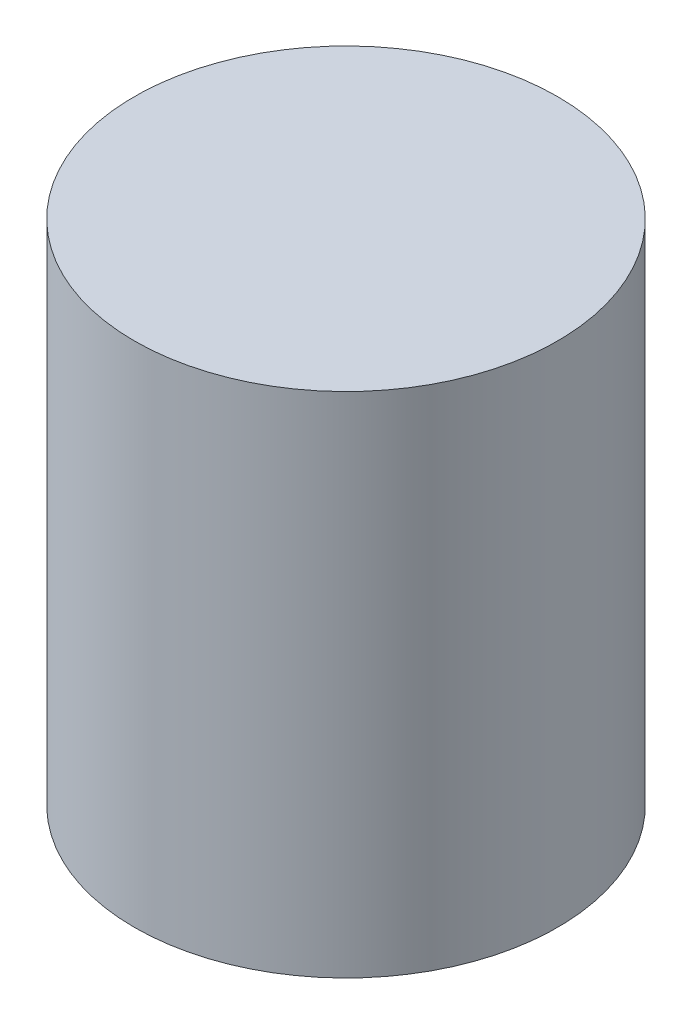
SolidWorks part; units mm, degrees
ref_plane "前视基准面" through (0, 0, 0) normal (0, 0, 1) x (1, 0, 0)
ref_plane "上视基准面" through (0, 0, 0) normal (0, 1, 0) x (1, 0, 0)
ref_plane "右视基准面" through (0, 0, 0) normal (1, 0, 0) x (0, 0, -1)
other "Configuration Table"
sketch "草图1" plane through (0, 0, 0) normal (0, 1, 0) x (1, 0, 0)
  circle A0 centre (0, 0) radius 25
  dimension "D1" = 50
extrude "凸台-拉伸1" add sketch "草图1" along normal blind 60
sketch "草图2" plane through (0, 0, 0) normal (0, -1, 0) x (1, 0, 0)
  circle A0 centre (0, 0) radius 22
  dimension "D1" = 44
extrude "切除-拉伸1" cut sketch "草图2" against normal blind 55
sketch "草图3" plane through (0, 0, 0) normal (0, -1, 0) x (1, 0, 0)
  circle A0 centre (0, 0) radius 22
  circle A1 centre (0, 0) radius 15
  dimension "D1" = 44
  dimension "D2" = 30
extrude "凸台-拉伸2" add sketch "草图3" against normal blind 3
